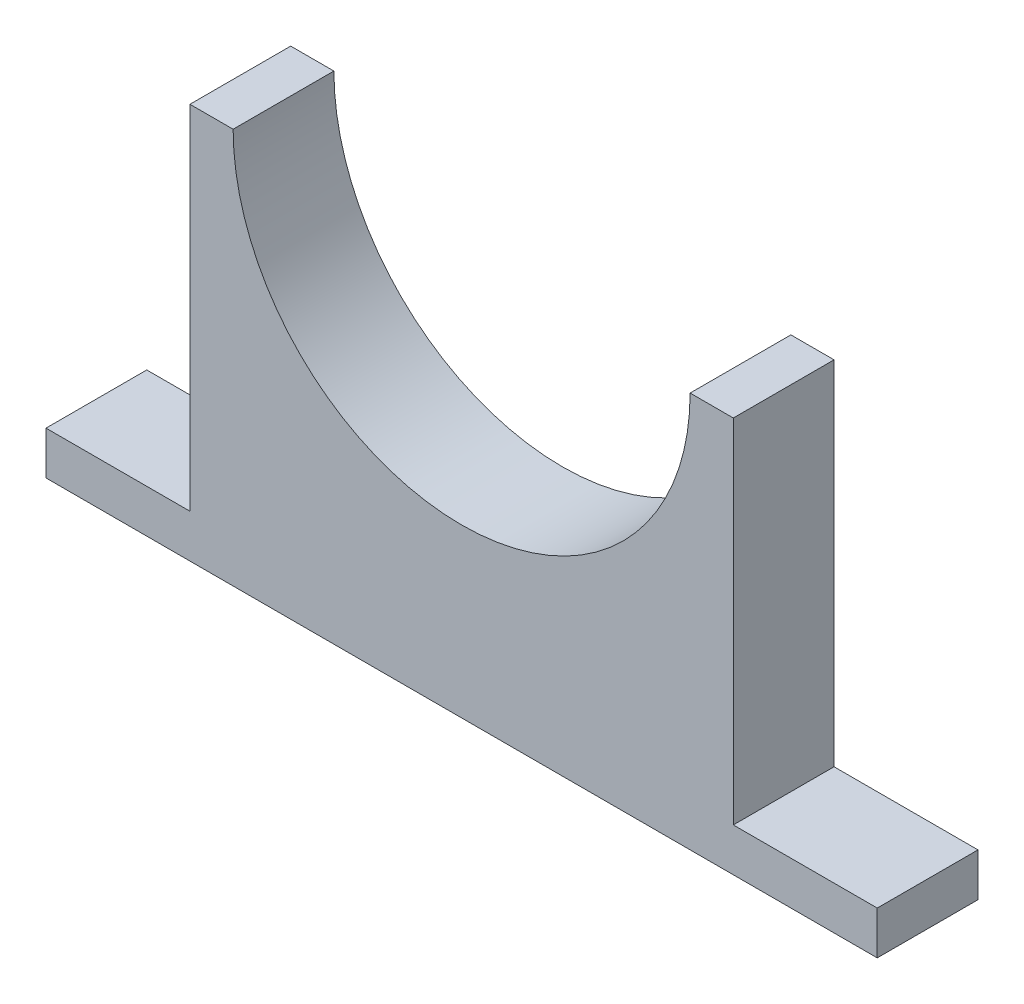
SolidWorks part; units mm, degrees
ref_plane "Front Plane" through (0, 0, 0) normal (0, 0, 1) x (1, 0, 0)
ref_plane "Top Plane" through (0, 0, 0) normal (0, 1, 0) x (1, 0, 0)
ref_plane "Right Plane" through (0, 0, 0) normal (1, 0, 0) x (0, 0, -1)
sketch "Sketch1" plane through (0, 0, 0) normal (0, 0, 1) x (1, 0, 0)
  line L0 (-15.875, 0) -> (-18.875, 0)
  line L1 (-18.875, 0) -> (-18.875, -24.485)
  line L2 (-18.875, -24.485) -> (-28.875, -24.485)
  line L3 (-28.875, -24.485) -> (-28.875, -27.485)
  line L4 (-28.875, -27.485) -> (28.875, -27.485)
  line L5 (28.875, -27.485) -> (28.875, -24.485)
  line L6 (28.875, -24.485) -> (18.875, -24.485)
  line L7 (18.875, -24.485) -> (18.875, 0)
  line L8 (18.875, 0) -> (15.875, 0)
  arc A0 (-15.875, 0) -> (15.875, 0) centre (0, 0) ccw
  dimension "D1" = 31.75
  dimension "D2" = 24.485
  dimension "D3" = 3
  dimension "D4" = 10
  dimension "D5" = 3
extrude "Boss-Extrude1" add sketch "Sketch1" along normal blind 7
